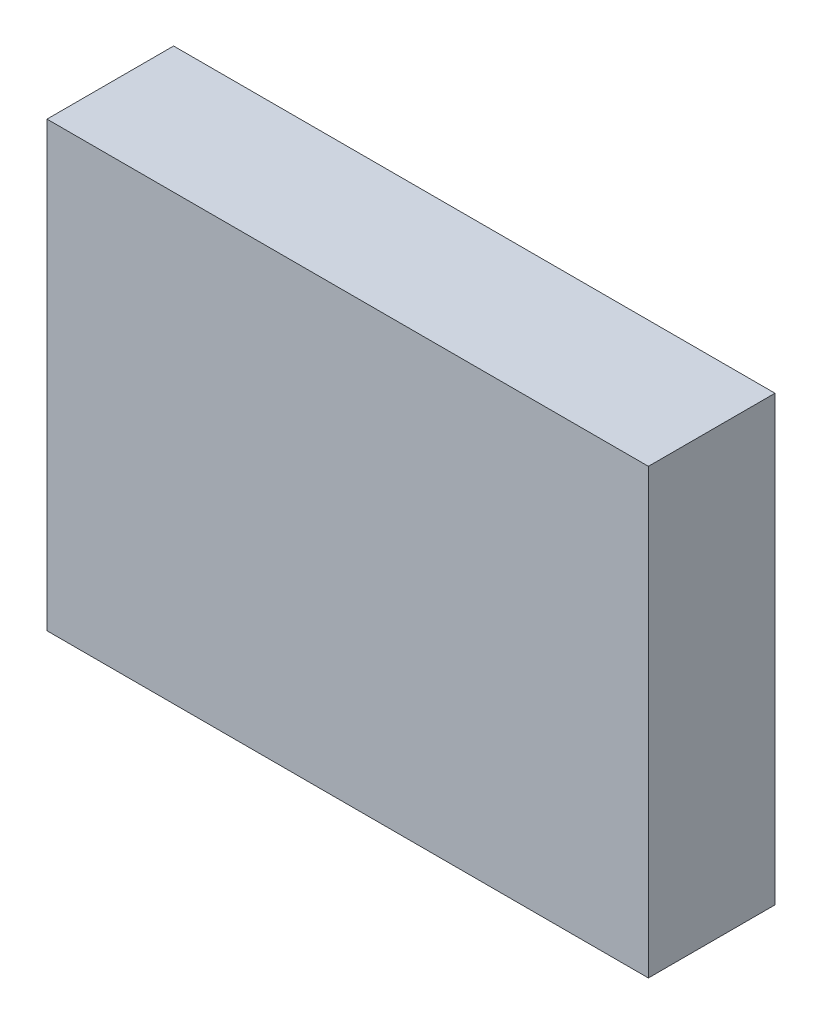
SolidWorks part; units mm, degrees
ref_plane "Front Plane" through (0, 0, 0) normal (0, 0, 1) x (1, 0, 0)
ref_plane "Top Plane" through (0, 0, 0) normal (0, 1, 0) x (1, 0, 0)
ref_plane "Right Plane" through (0, 0, 0) normal (1, 0, 0) x (0, 0, -1)
sketch "Sketch1" plane through (0, 0, 0) normal (0, 0, 1) x (1, 0, 0)
  line L1 (-81.99, 75.9466) -> (38.66, 75.9466)
  line L2 (-81.99, 75.9466) -> (-81.99, 164.8466)
  line L3 (-81.99, 164.8466) -> (38.66, 164.8466)
  line L4 (38.66, 75.9466) -> (38.66, 164.8466)
  line L5 (-81.99, 75.9466) -> (38.66, 164.8466) construction
  line L6 (-81.99, 164.8466) -> (38.66, 75.9466) construction
  point P0 (-21.665, 120.3966)
  dimension "D1" = 88.9
  dimension "D2" = 120.65
extrude "Boss-Extrude1" add sketch "Sketch1" along normal blind 25.4
